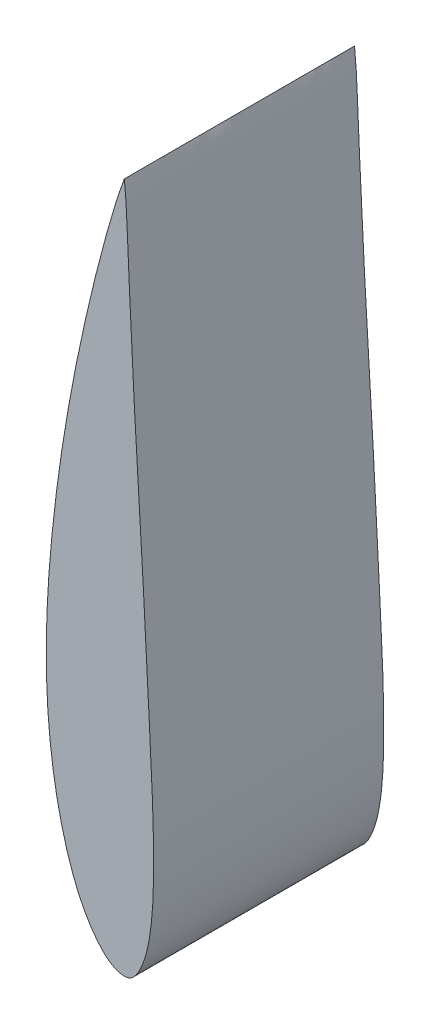
SolidWorks part; units mm, degrees
ref_plane "Ebene vorne" through (0, 0, 0) normal (1, 0, 0) x (0, 1, 0)
ref_plane "Ebene oben" through (0, 0, 0) normal (0, 0, 1) x (0, 1, 0)
ref_plane "Ebene rechts" through (0, 0, 0) normal (0, 1, 0) x (-1, 0, 0)
curve "Kurve1"
  spline degree 3 poles (0.9977, -0.0001, 0) (1.0006, -0.0001, 0) (0.9977, 0.0007, 0) (0.9954, 0.0018, 0) (0.9895, 0.0038, 0) (0.9824, 0.0063, 0) (0.9728, 0.0096, 0) (0.9613, 0.0133, 0) (0.9478, 0.0174, 0) (0.9324, 0.0219, 0) (0.9152, 0.0267, 0) (0.8961, 0.0319, 0) (0.8754, 0.0373, 0) (0.8531, 0.043, 0) (0.8292, 0.0488, 0) (0.804, 0.0547, 0) (0.7774, 0.0606, 0) (0.7497, 0.0665, 0) (0.7209, 0.0724, 0) (0.6911, 0.0781, 0) (0.6605, 0.0835, 0) (0.6293, 0.0887, 0) (0.5974, 0.0935, 0) (0.5652, 0.0979, 0) (0.5327, 0.1019, 0) (0.5, 0.1055, 0) (0.4674, 0.1085, 0) (0.4349, 0.1109, 0) (0.4026, 0.1126, 0) (0.3708, 0.1136, 0) (0.3395, 0.1137, 0) (0.3089, 0.1131, 0) (0.2791, 0.1116, 0) (0.2503, 0.1092, 0) (0.2226, 0.106, 0) (0.196, 0.1021, 0) (0.1707, 0.0975, 0) (0.1468, 0.0922, 0) (0.1245, 0.0863, 0) (0.1037, 0.08, 0) (0.0846, 0.0732, 0) (0.0674, 0.0658, 0) (0.0519, 0.058, 0) (0.0384, 0.0498, 0) (0.0268, 0.0417, 0) (0.0172, 0.0335, 0) (0.0096, 0.0254, 0) (0.0042, 0.017, 0) (0.0009, 0.0088, 0) (-0.0004, 0.0011, 0) (0.0006, -0.0057, 0) (0.0042, -0.0115, 0) (0.0099, -0.0164, 0) (0.0174, -0.0211, 0) (0.027, -0.0254, 0) (0.0386, -0.0295, 0) (0.0521, -0.0331, 0) (0.0675, -0.0361, 0) (0.0848, -0.0384, 0) (0.1039, -0.0401, 0) (0.1246, -0.0412, 0) (0.1469, -0.0418, 0) (0.1708, -0.0418, 0) (0.1961, -0.0415, 0) (0.2226, -0.0408, 0) (0.2504, -0.0398, 0) (0.2792, -0.0385, 0) (0.3089, -0.037, 0) (0.3395, -0.0355, 0) (0.3708, -0.0339, 0) (0.4026, -0.0323, 0) (0.4348, -0.0306, 0) (0.4673, -0.0289, 0) (0.5, -0.0271, 0) (0.5327, -0.0253, 0) (0.5652, -0.0234, 0) (0.5974, -0.0215, 0) (0.6292, -0.0196, 0) (0.6605, -0.0177, 0) (0.6911, -0.016, 0) (0.7208, -0.0143, 0) (0.7496, -0.0128, 0) (0.7774, -0.0114, 0) (0.8039, -0.0101, 0) (0.8292, -0.0089, 0) (0.853, -0.0078, 0) (0.8754, -0.0068, 0) (0.8961, -0.0059, 0) (0.9151, -0.005, 0) (0.9324, -0.0043, 0) (0.9478, -0.0037, 0) (0.9613, -0.003, 0) (0.9728, -0.0023, 0) (0.9823, -0.0016, 0) (0.9896, -0.001, 0) (0.9953, -0.0005, 0) (0.9977, -0.0001, 0) (1.0006, -0.0001, 0) (0.9977, 0.0007, 0) knots -0.004677 -0.002084 -0.000521 0 0.000552 0.002207 0.004953 0.008769 0.013624 0.019492 0.026331 0.034118 0.042815 0.05238 0.06278 0.073959 0.085865 0.098446 0.111647 0.125415 0.139681 0.154378 0.169447 0.184821 0.200433 0.216224 0.232117 0.248051 0.26396 0.279777 0.295442 0.310885 0.326054 0.340892 0.355349 0.369378 0.38293 0.395953 0.40841 0.420261 0.431467 0.441988 0.451799 0.46091 0.469304 0.476946 0.483798 0.489858 0.495198 0.499997 0.504304 0.507974 0.511123 0.514149 0.51765 0.521912 0.526982 0.532916 0.539692 0.547309 0.555757 0.565025 0.575098 0.58594 0.597509 0.609762 0.622649 0.636122 0.650118 0.664572 0.679425 0.694613 0.710068 0.725733 0.741529 0.757395 0.773262 0.789063 0.804734 0.820197 0.835393 0.850252 0.864712 0.878713 0.892194 0.905092 0.917358 0.92894 0.939788 0.949856 0.959093 0.967472 0.974955 0.981503 0.987099 0.99171 0.995323 0.997916 0.999479 1 1.000552 1.002207 1.004953 periodic
sketch "Skizze2" plane through (0, 0, 0) normal (0, 0, 1) x (0, 1, 0)
  line L0 (28.1262, -15.4664) -> (-1.8738, -15.4664) construction
  line L1 (-1.8738, -15.4664) -> (-1.8738, -10.7752) construction
  spline S1 degree 3 poles (28.0582, -15.4702) (28.1434, -15.4683) (28.0564, -15.4449) (27.9869, -15.4132) (27.8124, -15.3535) (27.5965, -15.2767) (27.3098, -15.1798) (26.9654, -15.0696) (26.5604, -14.9462) (26.0981, -14.8123) (25.5803, -14.6673) (25.0094, -14.5122) (24.3876, -14.3492) (23.7174, -14.1802) (23.0018, -14.0072) (22.2441, -13.8311) (21.4473, -13.6535) (20.6148, -13.4761) (19.7503, -13.3015) (18.8573, -13.1321) (17.9399, -12.9691) (17.0018, -12.815) (16.0471, -12.6709) (15.0798, -12.5386) (14.1042, -12.4196) (13.1245, -12.3142) (12.1447, -12.2252) (11.169, -12.154) (10.2017, -12.1028) (9.2469, -12.0739) (8.3087, -12.0696) (7.391, -12.0899) (6.4978, -12.1361) (5.6329, -12.2078) (4.8002, -12.3038) (4.0031, -12.4222) (3.245, -12.5612) (2.5294, -12.7207) (1.8589, -12.897) (1.2362, -13.0874) (0.6638, -13.2925) (0.1452, -13.5146) (-0.3178, -13.7502) (-0.7224, -13.9949) (-1.0697, -14.2393) (-1.3572, -14.4837) (-1.5866, -14.7286) (-1.7495, -14.9805) (-1.8469, -15.2275) (-1.8847, -15.4562) (-1.8553, -15.6624) (-1.7461, -15.8352) (-1.576, -15.9814) (-1.3504, -16.1217) (-1.0624, -16.2512) (-0.7163, -16.3739) (-0.3105, -16.4825) (0.153, -16.5706) (0.6716, -16.639) (1.2431, -16.6898) (1.8653, -16.7227) (2.5357, -16.7393) (3.2512, -16.7411) (4.0089, -16.7312) (4.8056, -16.7095) (5.6379, -16.677) (6.5024, -16.6372) (7.3951, -16.5926) (8.3123, -16.5458) (9.2502, -16.4981) (10.2048, -16.4492) (11.1718, -16.3988) (12.1473, -16.3465) (13.1269, -16.2925) (14.1064, -16.2366) (15.0819, -16.179) (16.0489, -16.1211) (17.0034, -16.0629) (17.9412, -16.0061) (18.8585, -15.9528) (19.7512, -15.9021) (20.6157, -15.8557) (21.4481, -15.8128) (22.2448, -15.7733) (23.0024, -15.7368) (23.7177, -15.7029) (24.3878, -15.6721) (25.0096, -15.6444) (25.5805, -15.6195) (26.0981, -15.5983) (26.5601, -15.5781) (26.965, -15.5582) (27.3095, -15.5372) (27.5962, -15.5159) (27.8127, -15.4959) (27.9858, -15.4822) (28.0582, -15.4702) (28.1434, -15.4683) (28.0564, -15.4449) knots -0.004677 -0.002084 -0.000521 0 0.000552 0.002207 0.004953 0.008769 0.013624 0.019492 0.026331 0.034118 0.042815 0.05238 0.06278 0.073959 0.085865 0.098446 0.111647 0.125415 0.139681 0.154378 0.169447 0.184821 0.200433 0.216224 0.232117 0.248051 0.26396 0.279777 0.295442 0.310885 0.326054 0.340892 0.355349 0.369378 0.38293 0.395953 0.40841 0.420261 0.431467 0.441988 0.451799 0.46091 0.469304 0.476946 0.483798 0.489858 0.495198 0.499997 0.504304 0.507974 0.511123 0.514149 0.51765 0.521912 0.526982 0.532916 0.539692 0.547309 0.555757 0.565025 0.575098 0.58594 0.597509 0.609762 0.622649 0.636122 0.650118 0.664572 0.679425 0.694613 0.710068 0.725733 0.741529 0.757395 0.773262 0.789063 0.804734 0.820197 0.835393 0.850252 0.864712 0.878713 0.892194 0.905092 0.917358 0.92894 0.939788 0.949856 0.959093 0.967472 0.974955 0.981503 0.987099 0.99171 0.995323 0.997916 0.999479 1 1.000552 1.002207 1.004953 only from (28.1262, -15.4664) to (28.1262, -15.4664)
  point P1 (0, 0)
  point P3 (0, 0)
  dimension "D1" = 30
extrude "Aufsatz-Linear austragen1" add sketch "Skizze2" along normal blind 10 contours S1
